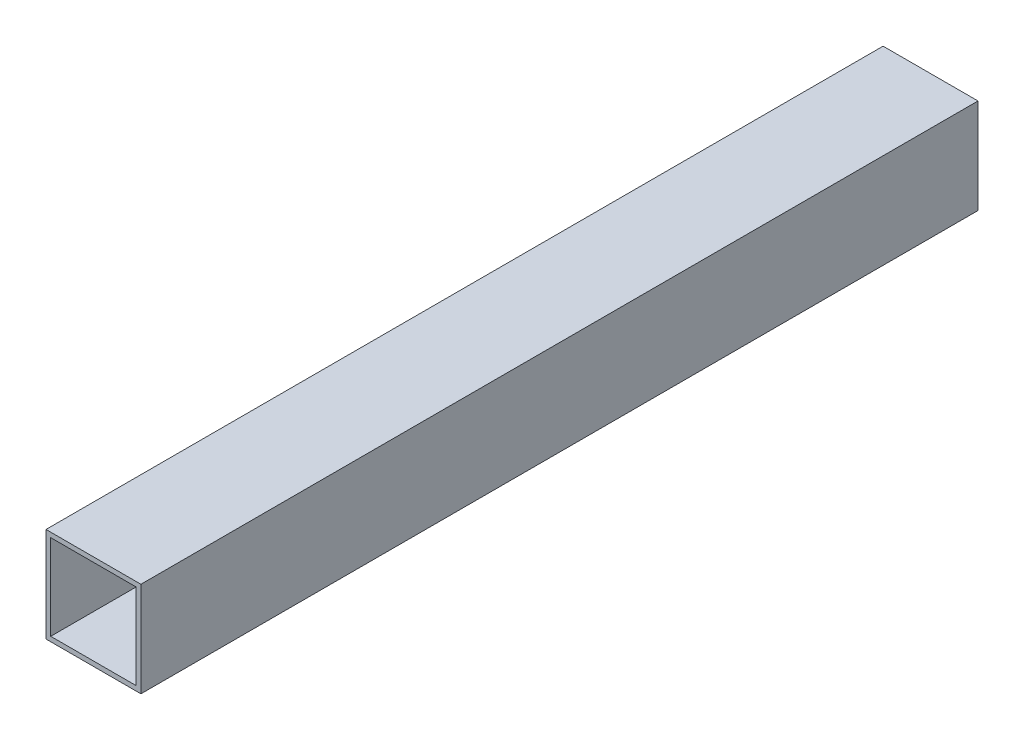
SolidWorks part; units mm, degrees
ref_plane "Front Plane" through (0, 0, 0) normal (0, 0, 1) x (1, 0, 0)
ref_plane "Top Plane" through (0, 0, 0) normal (0, 1, 0) x (1, 0, 0)
ref_plane "Right Plane" through (0, 0, 0) normal (1, 0, 0) x (0, 0, -1)
sketch "Sketch1" plane through (0, 0, 0) normal (0, 0, 1) x (1, 0, 0)
  line L5 (-15.875, 15.875) -> (15.875, 15.875)
  line L6 (-15.875, 15.875) -> (-15.875, -15.875)
  line L11 (-15.875, -15.875) -> (15.875, -15.875)
  line L12 (15.875, 15.875) -> (15.875, -15.875)
  line L13 (-15.875, 15.875) -> (15.875, -15.875) construction
  line L14 (-15.875, -15.875) -> (15.875, 15.875) construction
  line L15 (-14.2875, 14.2875) -> (14.2875, 14.2875)
  line L16 (-14.2875, 14.2875) -> (-14.2875, -14.2875)
  line L17 (-14.2875, -14.2875) -> (14.2875, -14.2875)
  line L18 (14.2875, 14.2875) -> (14.2875, -14.2875)
  line L19 (-14.2875, 14.2875) -> (14.2875, -14.2875) construction
  line L20 (-14.2875, -14.2875) -> (14.2875, 14.2875) construction
  point P0 (0, 0)
  point P6 (0, 0)
  dimension "D1" = 31.75
  dimension "D2" = 31.75
  dimension "D3" = 1.5875
extrude "Boss-Extrude1" add sketch "Sketch1" along normal blind 280
